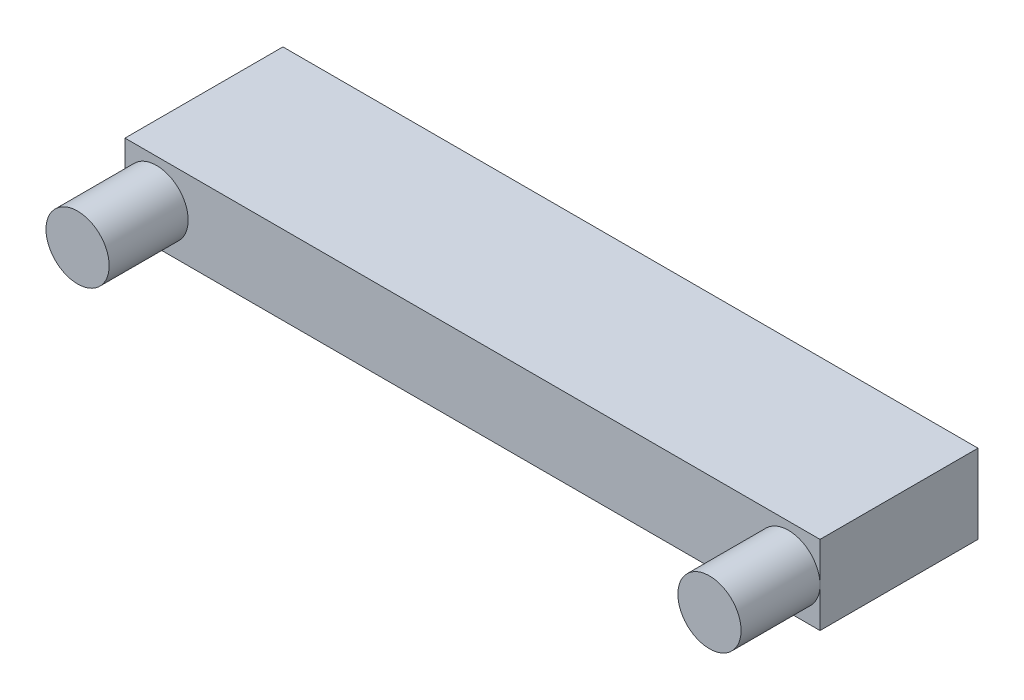
SolidWorks part; units mm, degrees
ref_plane "Alzado" through (0, 0, 0) normal (0, 0, 1) x (1, 0, 0)
ref_plane "Planta" through (0, 0, 0) normal (0, 1, 0) x (1, 0, 0)
ref_plane "Vista lateral" through (0, 0, 0) normal (1, 0, 0) x (0, 0, -1)
sketch "Croquis1" plane through (0, 0, 0) normal (0, 0, 1) x (1, 0, 0)
  line L1 (-22, -2.5) -> (22, -2.5)
  line L2 (-22, -2.5) -> (-22, 2.5)
  line L3 (-22, 2.5) -> (22, 2.5)
  line L4 (22, -2.5) -> (22, 2.5)
  line L5 (-22, -2.5) -> (22, 2.5) construction
  line L6 (-22, 2.5) -> (22, -2.5) construction
  point P0 (0, 0)
extrude "Saliente-Extruir1" add sketch "Croquis1" along normal blind 10
sketch "Croquis2" plane through (0, 0, 10) normal (0, 0, 1) x (1, 0, 0)
  line L0 (22, -2.5) -> (22, 2.5) construction
  line L1 (-22, 2.5) -> (-22, -2.5) construction
  circle A0 centre (-20, 0) radius 2
  circle A1 centre (20, 0) radius 2
  point P2 (22, 0)
  point P7 (-22, 0)
  dimension "D1" = 2
  dimension "D2" = 2
extrude "Saliente-Extruir2" add sketch "Croquis2" along normal blind 5
